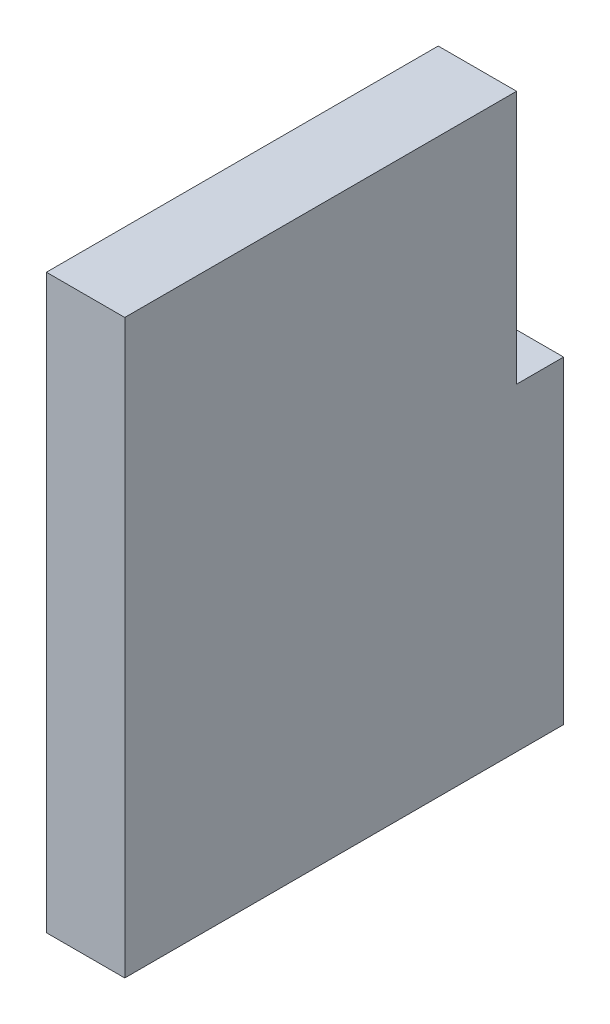
SolidWorks part; units mm, degrees
ref_plane "Front Plane" through (0, 0, 0) normal (0, 0, 1) x (1, 0, 0)
ref_plane "Top Plane" through (0, 0, 0) normal (0, 1, 0) x (1, 0, 0)
ref_plane "Right Plane" through (0, 0, 0) normal (1, 0, 0) x (0, 0, -1)
sketch "Sketch1" plane through (0, 0, 0) normal (0, 1, 0) x (1, 0, 0)
  line L1 (0, 0) -> (20, 0)
  line L2 (0, 0) -> (0, -100)
  line L3 (0, -100) -> (20, -100)
  line L4 (20, 0) -> (20, -100)
extrude "Boss-Extrude1" add sketch "Sketch1" along normal blind 146
sketch "Sketch2" plane through (0, 0, 0) normal (0, 0, -1) x (-1, 0, 0)
  line L0 (-20, 146) -> (-20, 0) construction
  line L1 (0, 0) -> (-20, 0)
  line L2 (0, 0) -> (0, 81.25)
  line L3 (0, 81.25) -> (-20, 81.25)
  line L4 (-20, 0) -> (-20, 81.25)
  dimension "D1" = 81.25
extrude "Boss-Extrude2" add sketch "Sketch2" along normal blind 12
